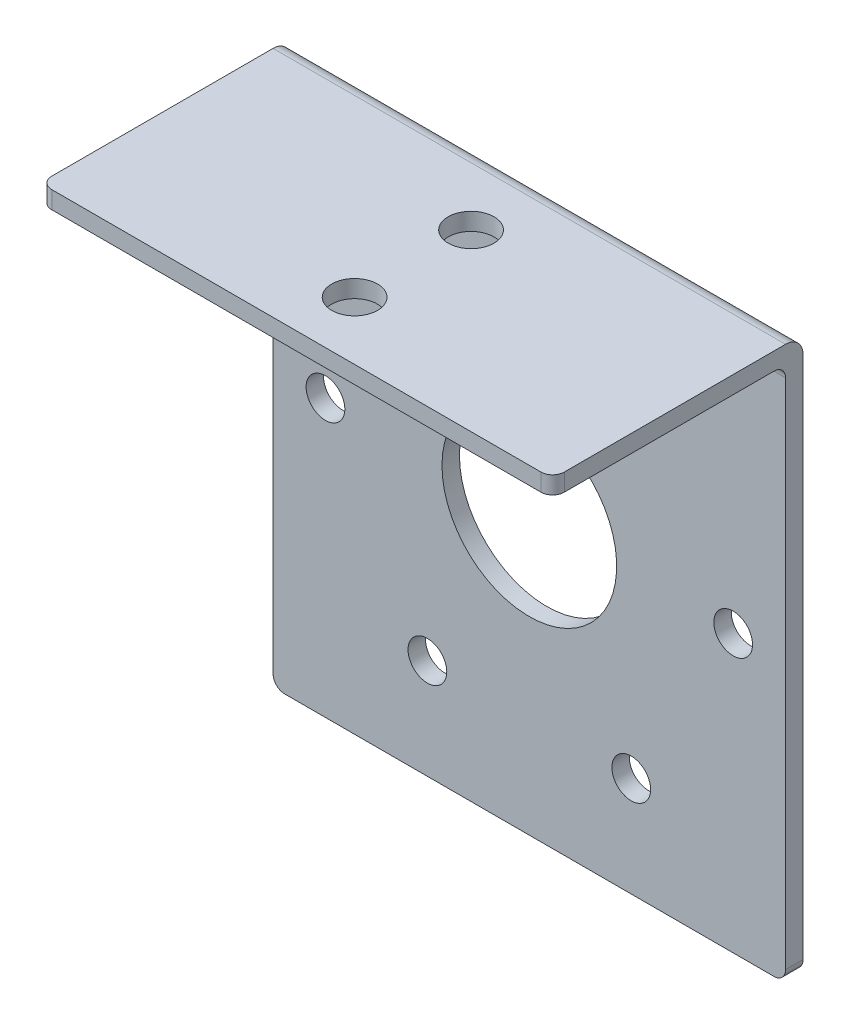
SolidWorks part; units mm, degrees
ref_plane "Front Plane" through (0, 0, 0) normal (0, 0, 1) x (1, 0, 0)
ref_plane "Top Plane" through (0, 0, 0) normal (0, 1, 0) x (1, 0, 0)
ref_plane "Right Plane" through (0, 0, 0) normal (1, 0, 0) x (0, 0, -1)
sketch "Sketch1" plane through (0, 0, 0) normal (0, 0, 1) x (1, 0, 0)
  line L1 (-44, -47.5) -> (44, -47.5)
  line L2 (-44, -47.5) -> (-44, 47.5)
  line L3 (-44, 47.5) -> (44, 47.5)
  line L4 (44, -47.5) -> (44, 47.5)
  line L5 (-44, -47.5) -> (44, 47.5) construction
  line L6 (-44, 47.5) -> (44, -47.5) construction
  point P0 (0, 0)
  dimension "D1" = 88
  dimension "D2" = 95
extrude "Boss-Extrude1" add sketch "Sketch1" along normal blind 3
sketch "Sketch2" plane through (0, 0, 3) normal (0, 0, 1) x (1, 0, 0)
  line L0 (44, -47.5) -> (44, 47.5) construction
  line L1 (-44, 47.5) -> (44, 47.5)
  line L2 (-44, 47.5) -> (-44, 44.5)
  line L3 (-44, 44.5) -> (44, 44.5)
  line L4 (44, 47.5) -> (44, 44.5)
  dimension "D1" = 3
  dimension "D2" = 88
extrude "Boss-Extrude2" add sketch "Sketch2" along normal blind 40 and the other way blind 1
sketch "Sketch3" plane through (0, 0, 0) normal (0, 0, -1) x (-1, 0, 0)
  circle A0 centre (0, 0) radius 15
  dimension "D3" = 30
extrude "Cut-Extrude1" cut sketch "Sketch3" against normal blind 10
ref_point "Point1"
fillet "Fillet1" radius 3 1 edges at (0, 47.5, 0)
fillet "Fillet2" radius 2 1 edges at (0, 44.5, 3)
sketch "Sketch5" plane through (0, 47.5, 0) normal (0, 1, 0) x (1, 0, 0)
  line L0 (44, -3) -> (-44, -3) construction
  circle A0 centre (0, -13) radius 3.935
  dimension "D1" = 7.87
  dimension "D2" = 10
extrude "Cut-Extrude3" cut sketch "Sketch5" against normal blind 10
pattern_linear "LPattern1" count 2 spacing 20 along (0, 0, 1) of "Cut-Extrude3"
fillet "Fillet3" radius 2 4 edges at (44, -47.5, 1.5) (-44, -47.5, 1.5) (-44, 46, 43) (44, 46, 43)
sketch "Sketch6" plane through (0, 0, 3) normal (0, 0, 1) x (1, 0, 0)
  circle A0 centre (35, 0) radius 3.325
  dimension "D1" = 6.65
  dimension "D2" = 35
extrude "Cut-Extrude4" cut sketch "Sketch6" against normal blind 10
pattern_circular "CirPattern1" count 6 over 360 about axis through (0, 0, 0) along (0, 0, 1) of "Cut-Extrude4"
